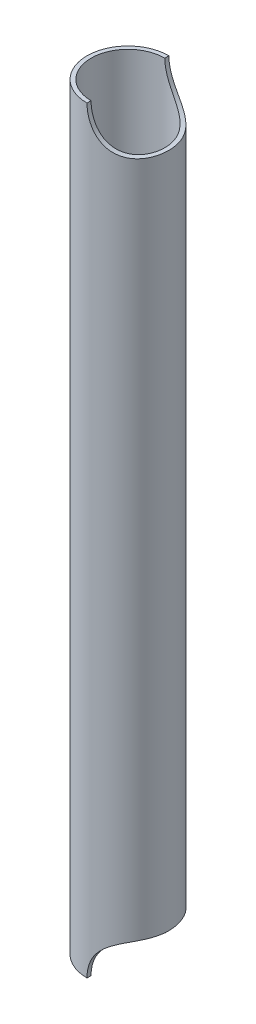
SolidWorks part; units mm, degrees
ref_plane "Front Plane" through (0, 0, 0) normal (0, 0, 1) x (1, 0, 0)
ref_plane "Top Plane" through (0, 0, 0) normal (0, 1, 0) x (1, 0, 0)
ref_plane "Right Plane" through (0, 0, 0) normal (1, 0, 0) x (0, 0, -1)
sketch "Sketch1" plane through (0, 0, 0) normal (0, 1, 0) x (1, 0, 0)
  circle A0 centre (0, 0) radius 18
  circle A1 centre (0, 0) radius 20
  dimension "D1" = 36
  dimension "D2" = 40
extrude "Boss-Extrude1" add sketch "Sketch1" along normal blind 370
sketch "Sketch2" plane through (0, 0, 0) normal (0, 0, 1) x (1, 0, 0)
  line L0 (-18, 0) -> (18, 0) construction
  line L1 (20, 0) -> (20, 370) construction
  line L2 (0, 370) -> (0, 0) construction
  line L3 (20, 370) -> (-20, 370) construction
  line L4 (0, 0) -> (20, 0)
  line L5 (20, 0) -> (20, 20)
  line L6 (-20, 0) -> (-20, 370)
  line L7 (20, 370) -> (20, 0)
  line L8 (20, 370) -> (20, 0)
  line L9 (-20, 0) -> (-20, 370)
  line L10 (-20, 185) -> (20, 185) construction
  line L11 (20, 370) -> (20, 350)
  line L12 (0, 370) -> (20, 370)
  arc A0 (0, 0) -> (20, 20) centre (20, 0) cw
  arc A1 (0, 370) -> (20, 350) centre (20, 370) ccw
extrude "Cut-Extrude1" cut sketch "Sketch2" against normal mid plane 50 contours A0 L4 L5 | L12 A1 L8
